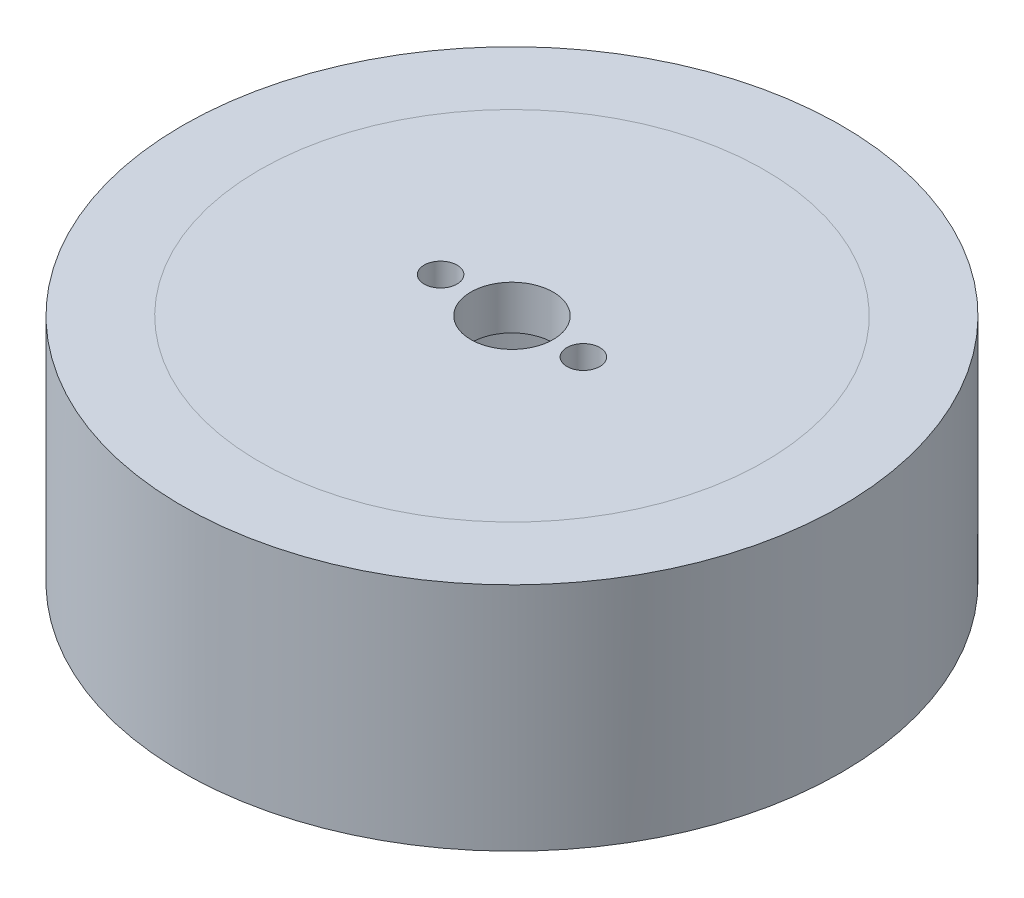
SolidWorks part; units mm, degrees
material "6061 合金"
ref_plane "前视基准面" through (0, 0, 0) normal (0, 0, 1) x (1, 0, 0)
ref_plane "上视基准面" through (0, 0, 0) normal (0, 1, 0) x (1, 0, 0)
ref_plane "右视基准面" through (0, 0, 0) normal (1, 0, 0) x (0, 0, -1)
sketch "草图1" plane through (0, 0, 0) normal (0, 0, 1) x (1, 0, 0)
  line L0 (0, 0) -> (0, -4)
  line L1 (0, -4) -> (-21, -4)
  line L2 (-21, -4) -> (-21, -21)
  line L3 (-21, -21) -> (-23, -21)
  line L4 (-23, -21) -> (-23, 0)
  line L5 (-23, 0) -> (0, 0)
  dimension "D1" = 23
  dimension "D2" = 21
  dimension "D3" = 21
  dimension "D4" = 4
revolve "旋转1" add sketch "草图1" angle 360 about L0
sketch "草图2" plane through (0, 0, 0) normal (0, 1, 0) x (1, 0, 0)
  line L0 (0, 0) -> (0, 6.5) construction
  circle A0 centre (0, 0) radius 3.75
  circle A1 centre (0, 0) radius 6.5 construction
  circle A2 centre (-6.5, 0) radius 1.5
  circle A3 centre (6.5, 0) radius 1.5
  dimension "D1" = 3
  dimension "D2" = 13
  dimension "D3" = 7.5
extrude "切除-拉伸1" cut sketch "草图2" against normal through all both and the other way through all
sketch "草图3" plane through (0, 0, 0) normal (0, 1, 0) x (1, 0, 0)
  circle A0 centre (0, 0) radius 30
  circle A1 centre (0, 0) radius 23
  circle A2 centre (0, 0) radius 23 construction
  dimension "D1" = 60
extrude "凸台-拉伸1" add sketch "草图3" against normal up to surface (21 mm away) separate body up to face at (-21, -21, 0)
